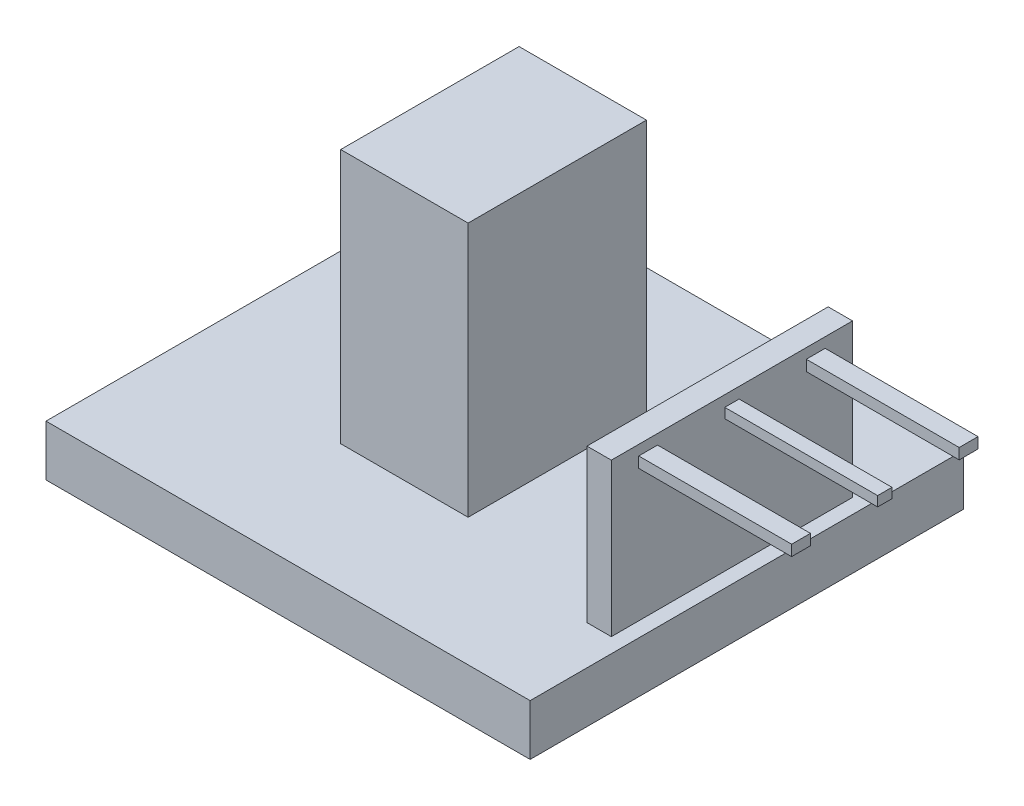
SolidWorks part; units mm, degrees
ref_plane "Plan de face" through (0, 0, 0) normal (0, 0, 1) x (1, 0, 0)
ref_plane "Plan de dessus" through (0, 0, 0) normal (0, 1, 0) x (1, 0, 0)
ref_plane "Plan de droite" through (0, 0, 0) normal (1, 0, 0) x (0, 0, -1)
sketch "Esquisse1" plane through (0, 0, 0) normal (0, 1, 0) x (1, 0, 0)
  line L1 (-9.5, 8.5) -> (9.5, 8.5)
  line L2 (-9.5, 8.5) -> (-9.5, -8.5)
  line L3 (-9.5, -8.5) -> (9.5, -8.5)
  line L4 (9.5, 8.5) -> (9.5, -8.5)
  line L5 (-9.5, 8.5) -> (9.5, -8.5) construction
  line L6 (-9.5, -8.5) -> (9.5, 8.5) construction
  point P0 (0, 0)
  dimension "D1" = 17
  dimension "D2" = 19
extrude "Boss.-Extru.1" add sketch "Esquisse1" along normal blind 2
sketch "Esquisse2" plane through (0, 2, 0) normal (0, 1, 0) x (1, 0, 0)
  line L1 (7.9643, 4.7331) -> (8.92, 4.7331)
  line L2 (7.9643, 4.7331) -> (7.9643, -4.7331)
  line L3 (7.9643, -4.7331) -> (8.92, -4.7331)
  line L4 (8.92, 4.7331) -> (8.92, -4.7331)
  line L5 (7.9643, 4.7331) -> (8.92, -4.7331) construction
  line L6 (7.9643, -4.7331) -> (8.92, 4.7331) construction
  point P0 (8.4422, 0)
extrude "Boss.-Extru.2" add sketch "Esquisse2" along normal blind 6
sketch "Esquisse3" plane through (8.92, 0, 0) normal (1, 0, 0) x (0, 0, -1)
  line L1 (-3.6574, 7.6046) -> (-2.9189, 7.6046)
  line L2 (-3.6574, 7.6046) -> (-3.6574, 7.1826)
  line L3 (-3.6574, 7.1826) -> (-2.9189, 7.1826)
  line L4 (-2.9189, 7.6046) -> (-2.9189, 7.1826)
  line L5 (-3.6574, 7.6046) -> (-2.9189, 7.1826) construction
  line L6 (-3.6574, 7.1826) -> (-2.9189, 7.6046) construction
  point P0 (-3.2881, 7.3936)
extrude "Boss.-Extru.3" add sketch "Esquisse3" along normal blind 6
mirror "Symétrie1" about plane through (0, 0, 0) normal (0, 0, 1) of "Boss.-Extru.3"
sketch "Esquisse4" plane through (8.92, 0, 0) normal (1, 0, 0) x (0, 0, -1)
  line L2 (-0.2813, 7.5695) -> (0.2813, 7.5695)
  line L3 (-0.2813, 7.5695) -> (-0.2813, 7.1826)
  line L4 (-0.2813, 7.1826) -> (0.2813, 7.1826)
  line L5 (0.2813, 7.5695) -> (0.2813, 7.1826)
  line L6 (-0.2813, 7.5695) -> (0.2813, 7.1826) construction
  line L7 (-0.2813, 7.1826) -> (0.2813, 7.5695) construction
  point P2 (0, 7.376)
extrude "Boss.-Extru.4" add sketch "Esquisse4" along normal blind 6
sketch "Esquisse5" plane through (0, 2, 0) normal (0, 1, 0) x (1, 0, 0)
  line L1 (2.0522, -3.4856) -> (-2.9478, -3.4856)
  line L2 (2.0522, -3.4856) -> (2.0522, 3.5144)
  line L3 (2.0522, 3.5144) -> (-2.9478, 3.5144)
  line L4 (-2.9478, -3.4856) -> (-2.9478, 3.5144)
  line L5 (2.0522, -3.4856) -> (-2.9478, 3.5144) construction
  line L6 (2.0522, 3.5144) -> (-2.9478, -3.4856) construction
  point P0 (-0.4478, 0.0144)
  dimension "D1" = 7
  dimension "D2" = 5
extrude "Boss.-Extru.5" add sketch "Esquisse5" along normal blind 10
